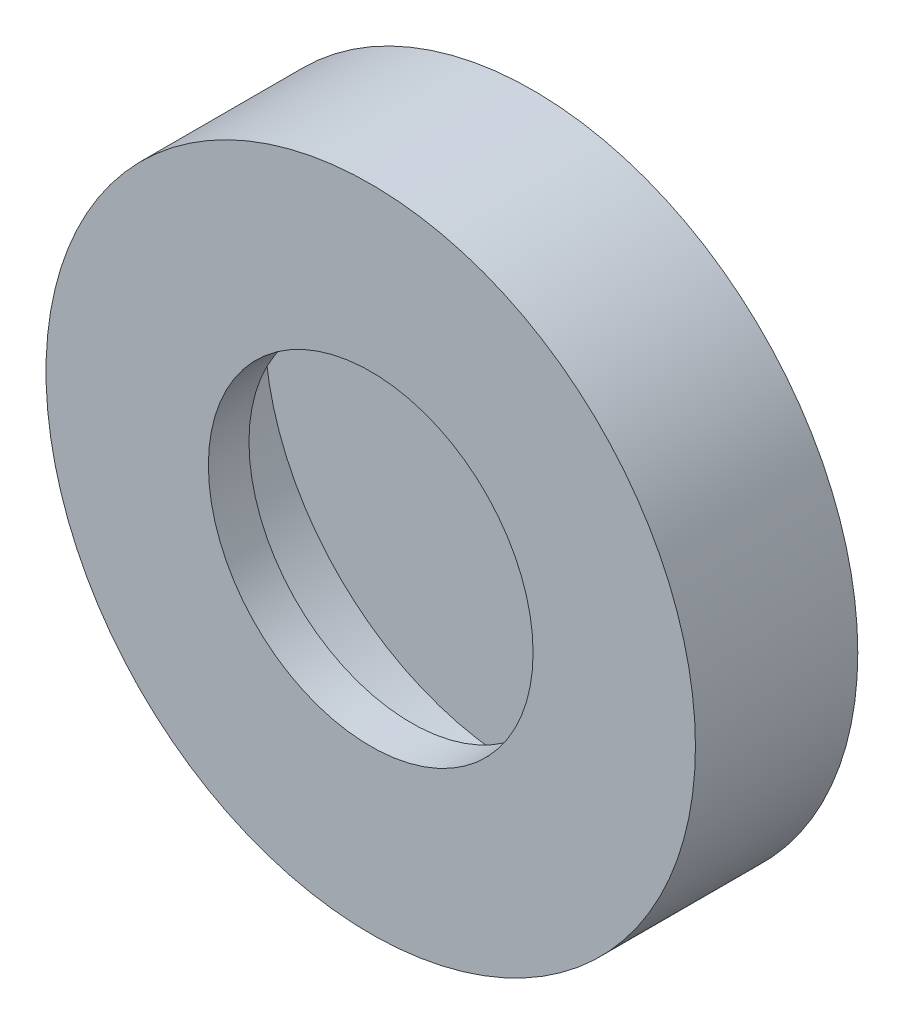
SolidWorks part; units mm, degrees
ref_plane "Plan de face" through (0, 0, 0) normal (0, 0, 1) x (1, 0, 0)
ref_plane "Plan de dessus" through (0, 0, 0) normal (0, 1, 0) x (1, 0, 0)
ref_plane "Plan de droite" through (0, 0, 0) normal (1, 0, 0) x (0, 0, -1)
sketch "Esquisse1" plane through (0, 0, 0) normal (0, 0, 1) x (1, 0, 0)
  circle A0 centre (0, 0) radius 50.8
extrude "Boss.-Extru.2" add sketch "Esquisse1" along normal blind 25.4
sketch "Esquisse4" plane through (0, 0, 25.4) normal (0, 0, 1) x (1, 0, 0)
  circle A0 centre (0, 0) radius 25.4
extrude "Enlèv. mat.-Extru.2" cut sketch "Esquisse4" against normal blind 6.35
sketch "Esquisse5" plane through (0, 0, 19.05) normal (0, 0, 1) x (1, 0, 0)
  circle A0 centre (0, 0) radius 40
extrude "Enlèv. mat.-Extru.3" cut sketch "Esquisse5" against normal blind 17.05
